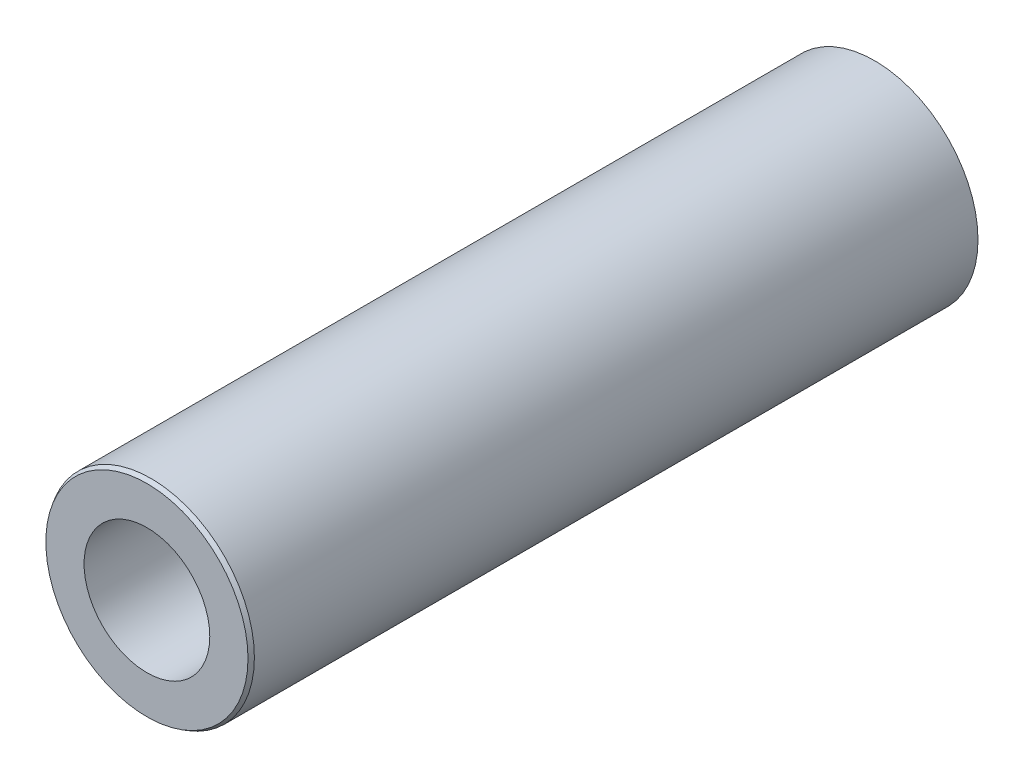
SolidWorks part; units mm, degrees
ref_plane "Front Plane" through (0, 0, 0) normal (0, 0, 1) x (1, 0, 0)
ref_plane "Top Plane" through (0, 0, 0) normal (0, 1, 0) x (1, 0, 0)
ref_plane "Right Plane" through (0, 0, 0) normal (1, 0, 0) x (0, 0, -1)
sketch "Sketch1" plane through (0, 0, 0) normal (0, 0, 1) x (1, 0, 0)
  circle A0 centre (33, 0) radius 2.55
  dimension "D1" = 5.1
extrude "Boss-Extrude1" add sketch "Sketch1" along normal blind 18
sketch "Sketch3" plane through (0, 0, 18) normal (0, 0, 1) x (1, 0, 0)
  circle A0 centre (33, 0) radius 1.55
  circle A1 centre (33, 0) radius 2.1
  dimension "D1" = 3.1
  dimension "D2" = 4.2
extrude "Cut-Extrude1" cut sketch "Sketch3" against normal up to next contours A0
chamfer "Chamfer1" distance 0.1 angle 30 2 edges at (35.55, 0, 18) (35.55, 0, 0)
equation "\"RingPostIn\"=5.1"
equation "\"D1@Sketch1\"=\"RingPostIn\""
equation "\"RingPinShaft\"= 5"
equation "\"CenterBearingOut\"=32.05"
equation "\"m3Thru\"=3.1"
equation "\"D1@Sketch3\"=\"m3Thru\""
equation "\"m3Insert\"=4.2"
equation "\"D2@Sketch3\"=\"m3Insert\""
